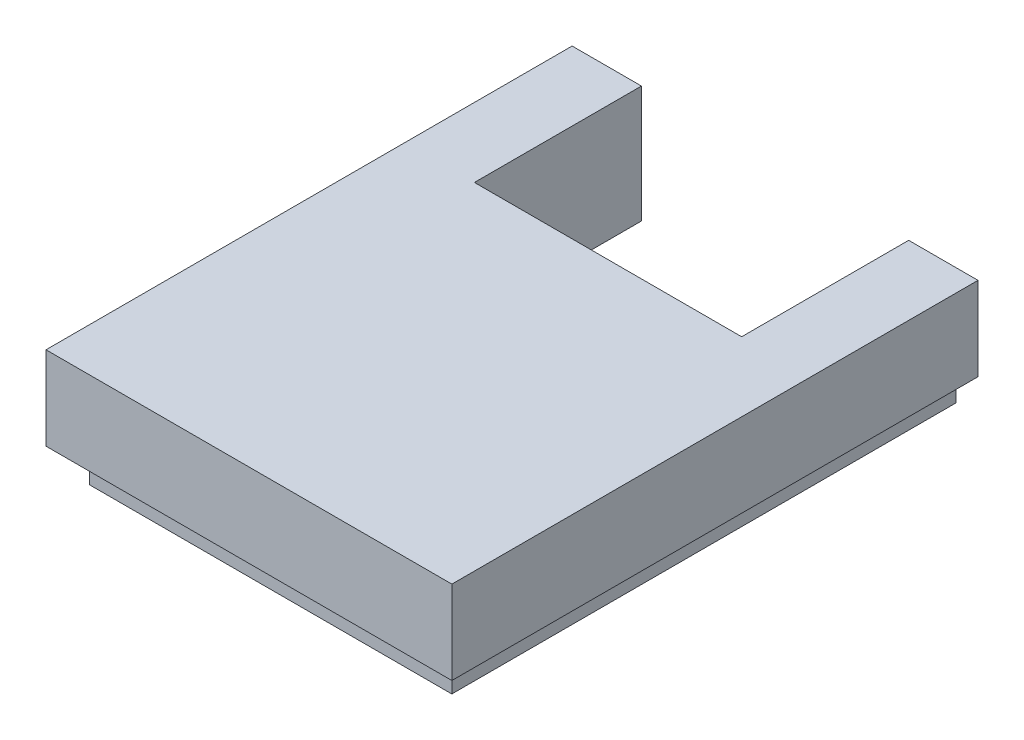
SolidWorks part; units mm, degrees
ref_plane "Front Plane" through (0, 0, 0) normal (0, 0, 1) x (1, 0, 0)
ref_plane "Top Plane" through (0, 0, 0) normal (0, 1, 0) x (1, 0, 0)
ref_plane "Right Plane" through (0, 0, 0) normal (1, 0, 0) x (0, 0, -1)
sketch "Sketch1" plane through (0, 0, 0) normal (0, 1, 0) x (1, 0, 0)
  line L0 (308.61, 400.05) -> (203.2, 400.05)
  line L1 (-203.2, 400.05) -> (-308.61, 400.05)
  line L2 (-308.61, 400.05) -> (-308.61, -400.05)
  line L3 (-308.61, -400.05) -> (308.61, -400.05)
  line L4 (308.61, 400.05) -> (308.61, -400.05)
  line L5 (-308.61, 400.05) -> (308.61, -400.05) construction
  line L6 (-308.61, -400.05) -> (308.61, 400.05) construction
  line L14 (-203.2, 400.05) -> (-203.2, 146.05)
  line L15 (-203.2, 146.05) -> (203.2, 146.05)
  line L16 (203.2, 400.05) -> (203.2, 146.05)
  point P0 (0, 0)
extrude "Boss-Extrude1" add sketch "Sketch1" along normal blind 177.8
sketch "Sketch2" plane through (0, 0, 0) normal (0, -1, 0) x (1, 0, 0)
  line L0 (308.61, -400.05) -> (275.5138, -400.05)
  line L1 (308.61, -400.05) -> (203.2, -400.05) construction
  line L2 (275.5138, -400.05) -> (275.5138, 367.0136)
  line L3 (-308.61, 400.05) -> (308.61, 400.05) construction
  line L4 (275.5138, 400.05) -> (308.61, 400.05)
  line L5 (308.61, 400.05) -> (308.61, -400.05)
  line L6 (-308.61, -400.05) -> (-275.6828, -400.05)
  line L7 (-203.2, -400.05) -> (-308.61, -400.05) construction
  line L8 (-275.6828, -400.05) -> (-275.6828, 367.0136)
  line L9 (-275.6828, 400.05) -> (-308.61, 400.05)
  line L10 (-308.61, 400.05) -> (-308.61, -400.05)
  line L12 (275.5138, 400.05) -> (-275.6828, 400.05)
  line L14 (275.5138, 367.0136) -> (-275.6828, 367.0136)
extrude "Cut-Extrude1" cut sketch "Sketch2" against normal blind 50.8
